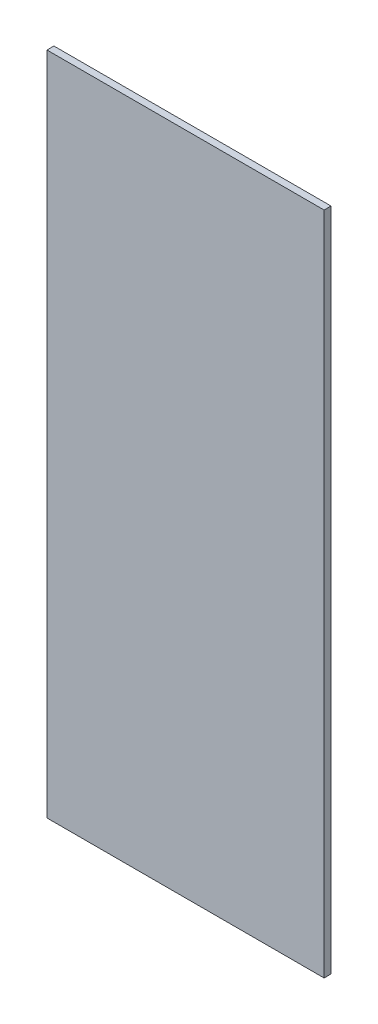
SolidWorks part; units mm, degrees
material "Acrylic (Medium-high impact)"
ref_plane "Front Plane" through (0, 0, 0) normal (0, 0, 1) x (1, 0, 0)
ref_plane "Top Plane" through (0, 0, 0) normal (0, 1, 0) x (1, 0, 0)
ref_plane "Right Plane" through (0, 0, 0) normal (1, 0, 0) x (0, 0, -1)
sketch "Sketch1" plane through (0, 0, 0) normal (0, 0, 1) x (1, 0, 0)
  line L1 (-63.5, 152.4) -> (63.5, 152.4)
  line L2 (-63.5, 152.4) -> (-63.5, -152.4)
  line L3 (-63.5, -152.4) -> (63.5, -152.4)
  line L4 (63.5, 152.4) -> (63.5, -152.4)
  line L5 (-63.5, 152.4) -> (63.5, -152.4) construction
  line L6 (-63.5, -152.4) -> (63.5, 152.4) construction
  point P0 (0, 0)
  dimension "D1" = 127
  dimension "D2" = 304.8
extrude "Boss-Extrude1" add sketch "Sketch1" along normal mid plane 3.175
